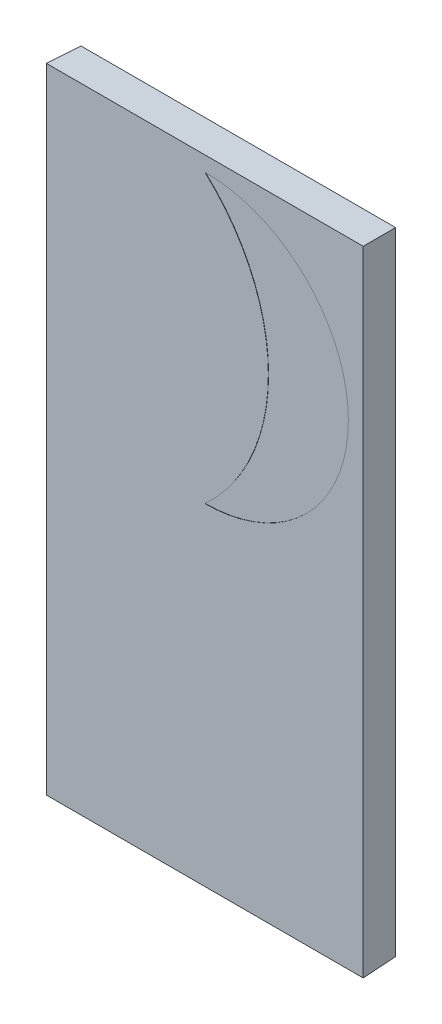
SolidWorks part; units mm, degrees
material "ABS"
ref_plane "Front Plane" through (0, 0, 0) normal (0, 0, 1) x (1, 0, 0)
ref_plane "Top Plane" through (0, 0, 0) normal (0, 1, 0) x (1, 0, 0)
ref_plane "Right Plane" through (0, 0, 0) normal (1, 0, 0) x (0, 0, -1)
sketch "Sketch1" plane through (0, 0, 0) normal (0, 0, 1) x (1, 0, 0)
  line L1 (-64, -128) -> (64, -128)
  line L2 (-64, -128) -> (-64, 128)
  line L3 (-64, 128) -> (64, 128)
  line L4 (64, -128) -> (64, 128)
  line L5 (-64, -128) -> (64, 128) construction
  line L6 (-64, 128) -> (64, -128) construction
  point P0 (0, 0)
  dimension "D1" = 128
  dimension "D2" = 256
extrude "Boss-Extrude1" add sketch "Sketch1" against normal blind 13.56 draft 2
sketch "Sketch2" plane through (0, 0, -13.56) normal (0, 0, -1) x (-1, 0, 0)
  line L0 (0, 0) -> (154.2731, 0) construction
  line L1 (-52.5265, -6.13) -> (52.5265, -6.13)
  line L2 (0, -152.6613) -> (0, 0) construction
  line L3 (52.5265, -6.13) -> (52.5265, -116.5265)
  line L4 (52.5265, -116.5265) -> (17, -116.5265)
  line L5 (17, -116.5265) -> (17, -120.6565)
  line L6 (17, -120.6565) -> (-17, -120.6565)
  line L7 (63.5265, 127.5265) -> (63.5265, -127.5265) construction
  line L8 (63.5265, -127.5265) -> (-63.5265, -127.5265) construction
  line L9 (-17, -116.5265) -> (-17, -120.6565)
  line L10 (-52.5265, -116.5265) -> (-17, -116.5265)
  line L11 (-52.5265, -6.13) -> (-52.5265, -116.5265)
  line L12 (-52.5265, 6.13) -> (-52.5265, 116.5265)
  line L13 (-52.5265, 116.5265) -> (-17, 116.5265)
  line L14 (-17, 116.5265) -> (-17, 120.6565)
  line L15 (17, 120.6565) -> (-17, 120.6565)
  line L16 (17, 116.5265) -> (17, 120.6565)
  line L17 (52.5265, 116.5265) -> (17, 116.5265)
  line L18 (52.5265, 6.13) -> (52.5265, 116.5265)
  line L19 (-52.5265, 6.13) -> (52.5265, 6.13)
  point P15 (0, -120.6565)
  point P18 (0, -6.13)
  dimension "D1" = 12.26
  dimension "D2" = 11
  dimension "D3" = 11
  dimension "D4" = 6.87
  dimension "D5" = 34
extrude "Cut-Extrude1" cut sketch "Sketch2" against normal blind 10.84
sketch "Sketch3" plane through (0, 0, -13.56) normal (0, 0, -1) x (-1, 0, 0)
  line L0 (104.0768, 0) -> (0, 0) construction
  line L1 (0, 0) -> (0, -140.2273) construction
  line L3 (63.5265, -127.5265) -> (-63.5265, -127.5265) construction
  circle A0 centre (56, -120.0265) radius 1.32
  circle A1 centre (56, 0) radius 1.32
  circle A2 centre (56, 120.0265) radius 1.32
  circle A3 centre (-56, -120.0265) radius 1.32
  circle A4 centre (-56, 0) radius 1.32
  circle A5 centre (-56, 120.0265) radius 1.32
  point P3 (56, -120.0265)
  dimension "D3" = 2.64
  dimension "D4" = 2.64
  dimension "D1" = 112
  dimension "D2" = 7.5
extrude "Cut-Extrude2" cut sketch "Sketch3" against normal blind 10
fillet "Fillet1" radius 10 4 edges at (-52.5265, 116.5265, -8.14) (52.5265, 116.5265, -8.14) (-52.5265, -116.5265, -8.14) (52.5265, -116.5265, -8.14)
fillet "Fillet2" radius 2 8 edges at (-17, -116.5265, -8.14) (-17, -120.6565, -8.14) (17, -116.5265, -8.14) (17, -120.6565, -8.14) (17, 116.5265, -8.14) (17, 120.6565, -8.14) (-17, 120.6565, -8.14) (-17, 116.5265, -8.14)
sketch "Sketch5" plane through (0, 0, 0) normal (0, 0, 1) x (1, 0, 0)
  line L0 (0, 0) -> (0, 128) construction
  line L1 (0, 0) -> (110.0635, 0) construction
  line L2 (64, 128) -> (-64, 128) construction
  line L4 (0, 64) -> (64, 64) construction
  line L5 (64, -128) -> (64, 128) construction
  circle A0 centre (0, 64) radius 57.9941
  circle A1 centre (-52.6604, 64) radius 78.3354
  point P14 (0, 121.9941)
extrude "Cut-Extrude3" cut sketch "Sketch5" against normal blind 0.1 contours A1 A0
equation "\"D4@Sketch3\"=\"D3@Sketch3\""
